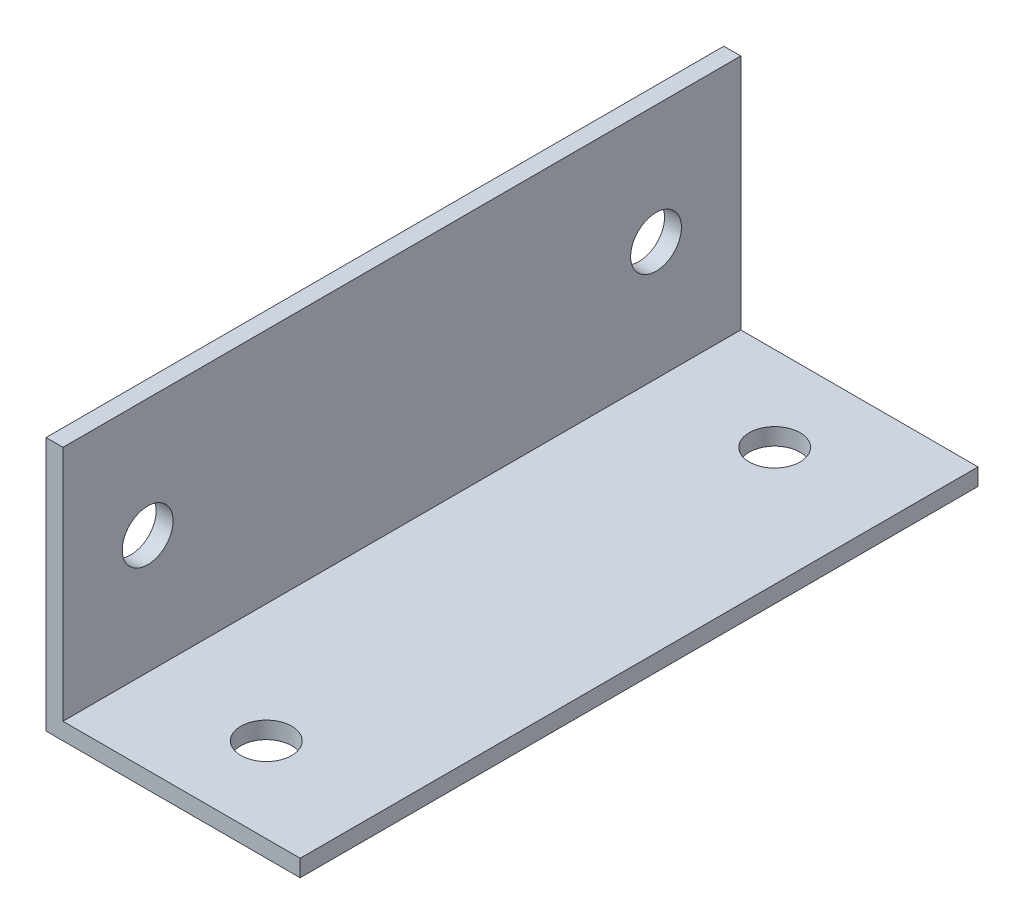
SolidWorks part; units mm, degrees
material "6061 合金"
ref_plane "前视基准面" through (0, 0, 0) normal (0, 0, 1) x (1, 0, 0)
ref_plane "上视基准面" through (0, 0, 0) normal (0, 1, 0) x (1, 0, 0)
ref_plane "右视基准面" through (0, 0, 0) normal (1, 0, 0) x (0, 0, -1)
sketch "草图1" plane through (0, 0, 0) normal (0, 0, 1) x (1, 0, 0)
  line L0 (0, 0) -> (0, 14)
  line L1 (0, 14) -> (-1, 14)
  line L2 (-1, 14) -> (-1, -1)
  line L3 (-1, -1) -> (14, -1)
  line L4 (14, -1) -> (14, 0)
  line L5 (14, 0) -> (0, 0)
  dimension "D1" = 15
  dimension "D2" = 15
  dimension "D3" = 1
extrude "凸台-拉伸1" add sketch "草图1" along normal blind 40
sketch "草图2" plane through (0, 0, 0) normal (0, 1, 0) x (1, 0, 0)
  line L0 (7, 0) -> (7, -40) construction
  line L1 (14, 0) -> (0, 0) construction
  line L2 (14, -40) -> (0, -40) construction
  line L3 (-1, -40) -> (-1, 0) construction
  line L4 (7, -20) -> (14, -20) construction
  line L5 (14, -40) -> (14, 0) construction
  circle A0 centre (7, -5) radius 1.5
  circle A1 centre (7, -35) radius 1.5
  dimension "D2" = 15
  dimension "D3" = 3
  dimension "D1" = 8
extrude "切除-拉伸1" cut sketch "草图2" against normal through all
ref_plane "基准面1" through (0, 0, 0) normal (-0.7071, 0.7071, 0) x (0, 0, 1)
mirror "镜向1" about plane through (0, 0, 0) normal (-0.7071, 0.7071, 0) of "切除-拉伸1"
